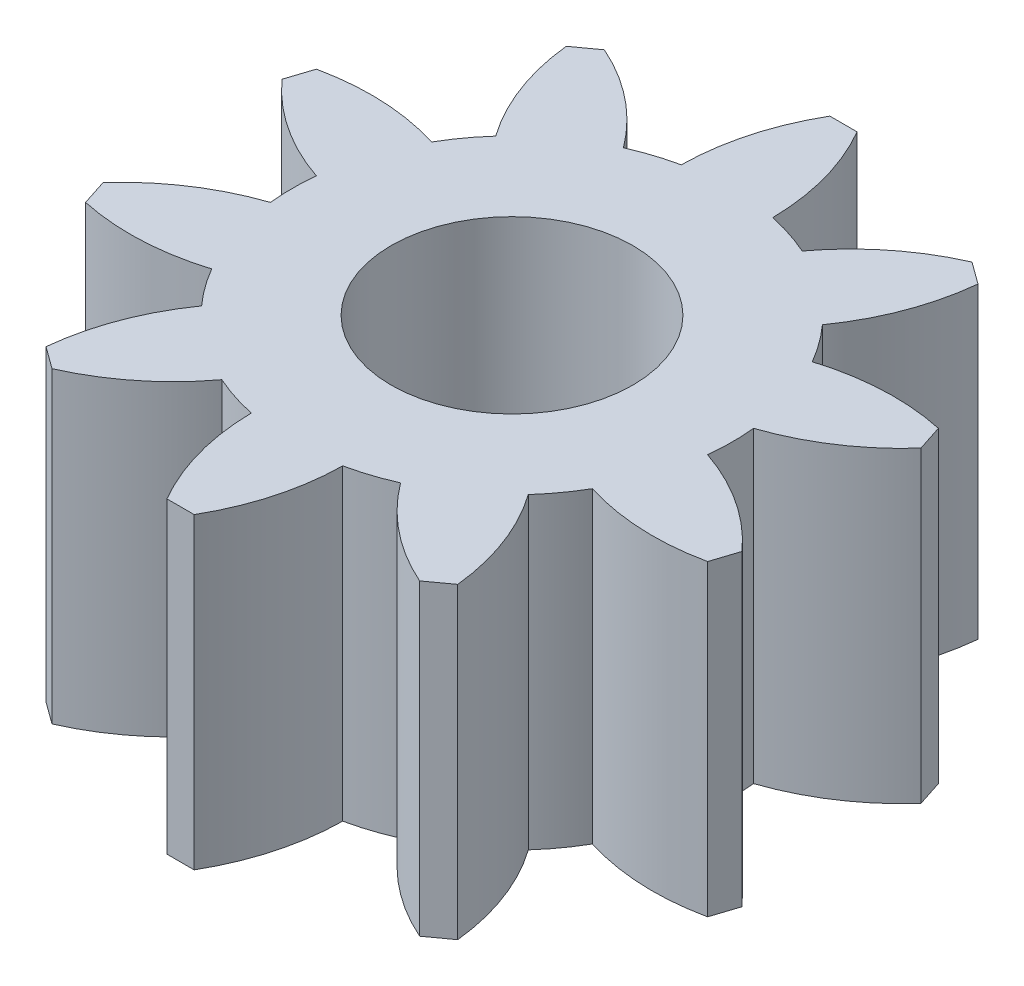
SolidWorks part; units mm, degrees
material "PLA"
ref_plane "Front Plane" through (0, 0, 0) normal (0, 0, 1) x (1, 0, 0)
ref_plane "Top Plane" through (0, 0, 0) normal (0, 1, 0) x (1, 0, 0)
ref_plane "Right Plane" through (0, 0, 0) normal (1, 0, 0) x (0, 0, -1)
sketch "Sketch1" plane through (0, 0, 0) normal (0, 1, 0) x (1, 0, 0)
  line L0 (0, 0) -> (0, 7.54) construction
  line L1 (0.31, 7.54) -> (-0.31, 7.54)
  line L2 (4.6827, 5.9178) -> (4.1811, 6.2822)
  line L3 (7.2668, 2.0352) -> (7.0752, 2.6248)
  line L4 (7.0752, -2.6248) -> (7.2668, -2.0352)
  line L5 (4.1811, -6.2822) -> (4.6827, -5.9178)
  line L6 (-0.31, -7.54) -> (0.31, -7.54)
  line L7 (-4.6827, -5.9178) -> (-4.1811, -6.2822)
  line L8 (-7.2668, -2.0352) -> (-7.0752, -2.6248)
  line L9 (-7.0752, 2.6248) -> (-7.2668, 2.0352)
  line L10 (-4.1811, 6.2822) -> (-4.6827, 5.9178)
  circle A0 centre (0, 0) radius 2.75
  circle A1 centre (0, 0) radius 5
  arc A2 (-0.31, 7.54) -> (-1.04, 4.8906) centre (4.3596, 4.8281) ccw
  arc A3 (0.31, 7.54) -> (1.04, 4.8906) centre (-4.3596, 4.8281) cw
  arc A4 (4.1811, 6.2822) -> (2.0333, 4.5679) centre (6.3649, 1.3435) ccw
  arc A5 (4.6827, 5.9178) -> (3.716, 3.3453) centre (-0.6891, 6.4685) cw
  arc A6 (7.0752, 2.6248) -> (4.3299, 2.5004) centre (5.939, -2.6543) ccw
  arc A7 (7.2668, 2.0352) -> (4.9727, 0.5222) centre (3.2446, 5.6382) cw
  arc A8 (7.2668, -2.0352) -> (4.9727, -0.5222) centre (3.2446, -5.6382) ccw
  arc A9 (7.0752, -2.6248) -> (4.3299, -2.5004) centre (5.939, 2.6543) cw
  arc A10 (4.6827, -5.9178) -> (3.716, -3.3453) centre (-0.6891, -6.4685) ccw
  arc A11 (4.1811, -6.2822) -> (2.0333, -4.5679) centre (6.3649, -1.3435) cw
  arc A12 (0.31, -7.54) -> (1.04, -4.8906) centre (-4.3596, -4.8281) ccw
  arc A13 (-0.31, -7.54) -> (-1.04, -4.8906) centre (4.3596, -4.8281) cw
  arc A14 (-4.1811, -6.2822) -> (-2.0333, -4.5679) centre (-6.3649, -1.3435) ccw
  arc A15 (-4.6827, -5.9178) -> (-3.716, -3.3453) centre (0.6891, -6.4685) cw
  arc A16 (-7.0752, -2.6248) -> (-4.3299, -2.5004) centre (-5.939, 2.6543) ccw
  arc A17 (-7.2668, -2.0352) -> (-4.9727, -0.5222) centre (-3.2446, -5.6382) cw
  arc A18 (-7.2668, 2.0352) -> (-4.9727, 0.5222) centre (-3.2446, 5.6382) ccw
  arc A19 (-7.0752, 2.6248) -> (-4.3299, 2.5004) centre (-5.939, -2.6543) cw
  arc A20 (-4.6827, 5.9178) -> (-3.716, 3.3453) centre (0.6891, 6.4685) ccw
  arc A21 (-4.1811, 6.2822) -> (-2.0333, 4.5679) centre (-6.3649, 1.3435) cw
  point P15 (0, 5)
  point P57 (0, 0)
  point P69 (0, 0)
  dimension "D1" = 5.5
  dimension "D2" = 10
  dimension "D4" = 1.04
  dimension "D5" = 5.4
  dimension "D3" = 0.31
  dimension "D6" = 2.54
  dimension "D7" = 10
extrude "Boss-Extrude1" add sketch "Sketch1" along normal blind 7
sketch "Sketch2" plane through (0, 0, 0) normal (0, -1, 0) x (1, 0, 0)
  circle A0 centre (0, 0) radius 2.75
  circle A1 centre (0, 0) radius 1.75
  dimension "D1" = 3.5
  dimension "D2" = 5.5
extrude "Boss-Extrude2" add sketch "Sketch2" against normal blind 2
